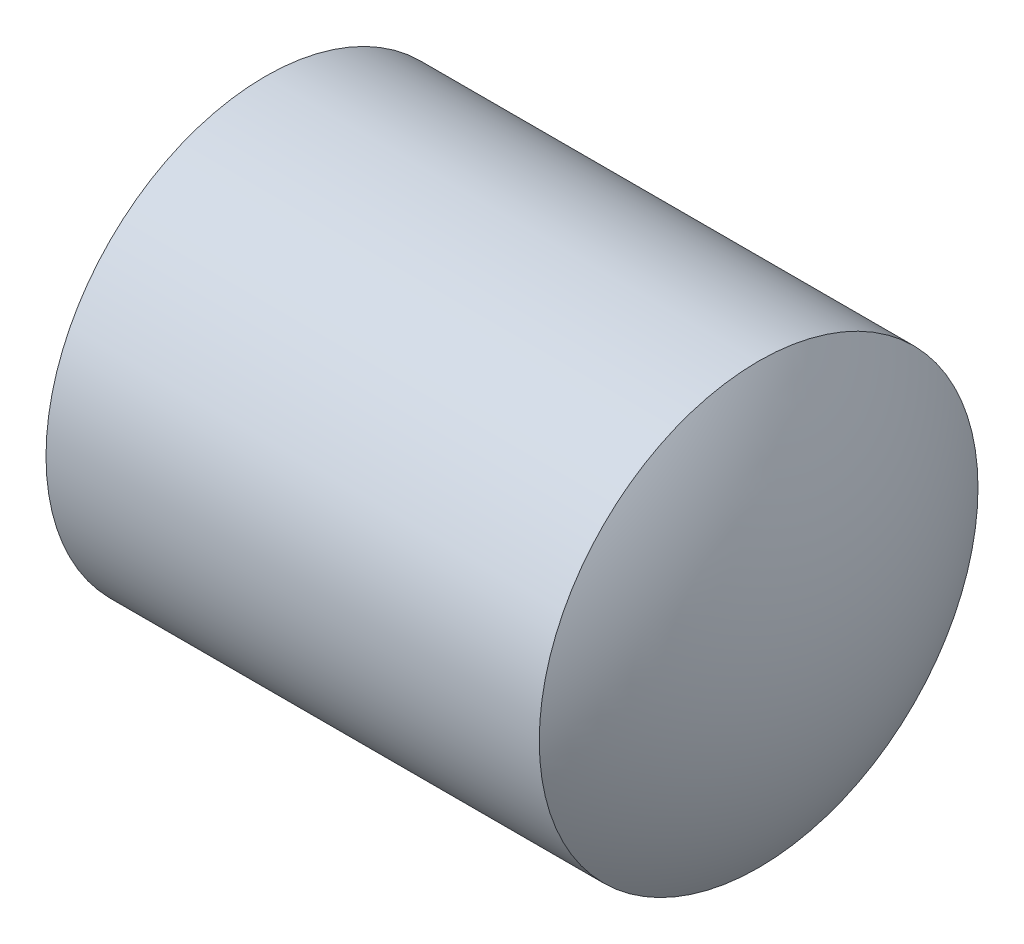
SolidWorks part; units mm, degrees
ref_plane "Plane1" through (0, 0, 0) normal (0, 0, 1) x (1, 0, 0)
ref_plane "Plane2" through (0, 0, 0) normal (0, 1, 0) x (1, 0, 0)
ref_plane "Plane3" through (0, 0, 0) normal (1, 0, 0) x (0, 0, -1)
sketch "BodySke" plane through (0, 0, 0) normal (0, 0, 1) x (1, 0, 0)
  line L0 (0, 0) -> (0, 1.2195)
  line L1 (0, 1.2195) -> (0.1619, 1.5)
  line L2 (0.1619, 1.5) -> (3.5346, 1.5)
  line L3 (0.5, 15.875) -> (0.5, -3.175) construction
  line L4 (4, 0) -> (0, 0)
  line L5 (-12.7, 0) -> (88.9, 0) construction
  line L8 (0, -1.2195) -> (0.1619, -1.5) construction
  arc A0 (4, 0) -> (3.5346, 1.5) centre (1.35, 0) ccw
  dimension "Oval_radius" = 2.65
  dimension "Length" = 4
  dimension "Diameter" = 3
  dimension "Drive_ch_ang" = 60
  dimension "Minor_dia" = 2.439
  dimension "Advance" = 0.5
revolve "BaseBody" add sketch "BodySke" angle 360 about L5
cosmetic thread "ThreadCosmetic" [suppressed] parameters "Thread_minor"=2.439
sketch "Sketch2" plane through (0, 0, 0) normal (-1, 0, 0) x (0, 0, 1)
  line L0 (0.433, 0.75) -> (-0.433, 0.75)
  line L1 (-0.433, 0.75) -> (-0.866, 0)
  line L2 (0.433, 0.75) -> (0.866, 0)
  line L3 (0.433, -0.75) -> (0.866, 0)
  line L4 (0.433, -0.75) -> (-0.433, -0.75)
  line L5 (-0.433, -0.75) -> (-0.866, 0)
  dimension "Hex_size" = 1.5
  dimension "D2" = 0.75
  dimension "D3" = 0.75
extrude "Hex" cut sketch "Sketch2" against normal blind 1.5
sketch "Sketch4" plane through (0, 4.7709, -0.5249) normal (-1, 0, 0) x (0, 0, 1)
  line L0 (0.5249, -4.7709) -> (1.3124, -4.7709)
  line L1 (0.5249, -4.7709) -> (6.6732, -1.2211) construction
  line L2 (0.5249, -4.7709) -> (0.9186, -4.0889)
  line L3 (1.153, -4.6137) -> (1.2782, -4.5415)
  line L4 (0.975, -4.3054) -> (1.1002, -4.2332)
  arc A0 (1.153, -4.6137) -> (0.975, -4.3054) centre (0.5249, -4.7709) ccw
  arc A1 (1.3124, -4.7709) -> (1.2782, -4.5415) centre (0.5249, -4.7709) ccw
  arc A2 (0.9186, -4.0889) -> (1.1002, -4.2332) centre (0.5249, -4.7709) cw
  circle A3 centre (0.5249, -4.7709) radius 0.6475 construction
  circle A4 centre (0.5249, -4.7709) radius 0.7875 construction
  dimension "D1" = 30
  dimension "Spline_n_dim" = 1.295
  dimension "Spline_m_dim" = 1.575
  dimension "Spline_a_dim" = 60
  dimension "D3" = 0.178
  dimension "Spline_p_dim" = 0.356
extrude "Spline6" [suppressed] cut sketch "Sketch4" against normal blind 1.2
pattern_circular "CirPattern1" [suppressed] count 6 every 60 about axis through (-12.7, 0, 0) along (1, 0, 0)
sketch "Sketch5" plane through (0, -2.3417, -0.7053) normal (-1, 0, 0) x (0, 0, 1)
  line L0 (0.7053, 2.3417) -> (1.4928, 2.3417)
  line L1 (0.7053, 2.3417) -> (5.7254, 7.3618) construction
  line L2 (0.7053, 2.3417) -> (0.7053, 3.1292)
  line L3 (1.289, 2.6736) -> (1.3736, 2.7582)
  line L4 (1.0373, 2.9254) -> (1.1218, 3.01)
  line L5 (1.0373, 2.9254) -> (1.289, 2.6736)
  arc A1 (1.4928, 2.3417) -> (1.3736, 2.7582) centre (0.7053, 2.3417) ccw
  arc A2 (0.7053, 3.1292) -> (1.1218, 3.01) centre (0.7053, 2.3417) cw
  circle A3 centre (0.7053, 2.3417) radius 0.6475 construction
  circle A4 centre (0.7053, 2.3417) radius 0.7875 construction
  dimension "D1" = 45
  dimension "Spline_n_dim" = 1.295
  dimension "Spline_m_dim" = 1.575
  dimension "Spline_a_dim" = 90
  dimension "D3" = 0.178
  dimension "Spline_p_dim" = 0.356
extrude "Spline4" [suppressed] cut sketch "Sketch5" against normal blind 1.2
pattern_circular "CirPattern2" [suppressed] count 4 every 90 about axis through (-12.7, 0, 0) along (1, 0, 0)
sketch "ThdSchSke" plane through (0, 0, 0) normal (0, 0, 1) x (1, 0, 0)
  line L0 (0.1619, -1.2195) -> (-0.0345, -1.5)
  line L1 (0.1619, -1.2195) -> (0.3584, -1.5)
  line L2 (0.3584, -1.5) -> (0.3584, -1.875)
  line L3 (-3.175, 0) -> (5.1513, 0) construction
  line L4 (0.1619, 1.5) -> (0.1619, -1.5) construction
  line L5 (0.3584, -1.875) -> (-0.0345, -1.875)
  line L6 (-0.0345, -1.875) -> (-0.0345, -1.5)
  dimension "Thread_minor" = 2.439
  dimension "Diameter" = 3
  dimension "SideAngle" = 55
  dimension "VeeAngle" = 70
  dimension "Overcut" = 3.75
revolve "ThreadSchematic" [suppressed] cut sketch "ThdSchSke" angle 360 about L3
pattern_linear "ThdSchPat" [suppressed]
equation "\"D2@Sketch2\" = \"Hex_size@Sketch2\" / 2"
equation "\"D3@Sketch2\" = \"Hex_size@Sketch2\" / 2"
equation "\"Thread_minor@ThreadCosmetic\" = \"Minor_dia@BodySke\""
equation "\"D1@Sketch4\" = \"Spline_a_dim@Sketch4\" / 2"
equation "\"D3@Sketch4\" = \"Spline_p_dim@Sketch4\" / 2"
equation "\"D2@CirPattern1\" = \"Spline_a_dim@Sketch4\""
equation "\"Num_teeth@CirPattern1\" = 360 / \"D2@CirPattern1\""
equation "\"Spline_a_dim@Sketch5\" = 90"
equation "\"Spline_p_dim@Sketch5\" = \"Spline_p_dim@Sketch4\""
equation "\"Spline_m_dim@Sketch5\" = \"Spline_m_dim@Sketch4\""
equation "\"Spline_n_dim@Sketch5\" = \"Spline_n_dim@Sketch4\""
equation "\"D1@Sketch5\" = \"Spline_a_dim@Sketch5\" / 2"
equation "\"D3@Sketch5\" = \"Spline_p_dim@Sketch5\" / 2"
equation "\"Key_eng@Spline4\" = \"Key_eng@Spline6\""
equation "\"Thread_minor@ThdSchSke\" = \"Thread_minor@ThreadCosmetic\""
equation "\"Diameter@ThdSchSke\" = \"Diameter@BodySke\""
equation "\"Overcut@ThdSchSke\" = \"Diameter@BodySke\" * 1.25"
equation "\"Num_threads@ThdSchPat\" = int( (\"Length@BodySke\" - ( ( ( \"Diameter@BodySke\" - \"Minor_dia@BodySke\" ) * 0.5 ) / tan( \"Drive_ch_ang@BodySke\" * 0.017453292 ) ) - ( \"Oval_radius@BodySke\" - sqr ( ( \"Oval_radius@BodySke\" * \"Oval_radius@BodySke\" ) - ( ( \"Diameter@BodySke\" * 0.5 ) * ( \"Diameter@BodySke\" * 0.5 ) ) ) ) ) / \"Advance@BodySke\" + 0.999 )  + 1"
equation "\"Advance@ThdSchPat\" = (\"Length@BodySke\" - ( ( ( \"Diameter@BodySke\" - \"Minor_dia@BodySke\" ) * 0.5 ) / tan( \"Drive_ch_ang@BodySke\" * 0.017453292 ) ) - ( \"Oval_radius@BodySke\" - sqr ( ( \"Oval_radius@BodySke\" * \"Oval_radius@BodySke\" ) - ( ( \"Diameter@BodySke\" * 0.5 ) * ( \"Diameter@BodySke\" * 0.5 ) ) ) ) ) /  (\"Num_threads@ThdSchPat\" - 1) 'relax it"
equation "' \"Num_threads@ThdSchPat\" = \"Num_threads@ThdSchPat\" - sgn( \"Num_threads@ThdSchPat\" - 1) '---chamfered tips only---"
